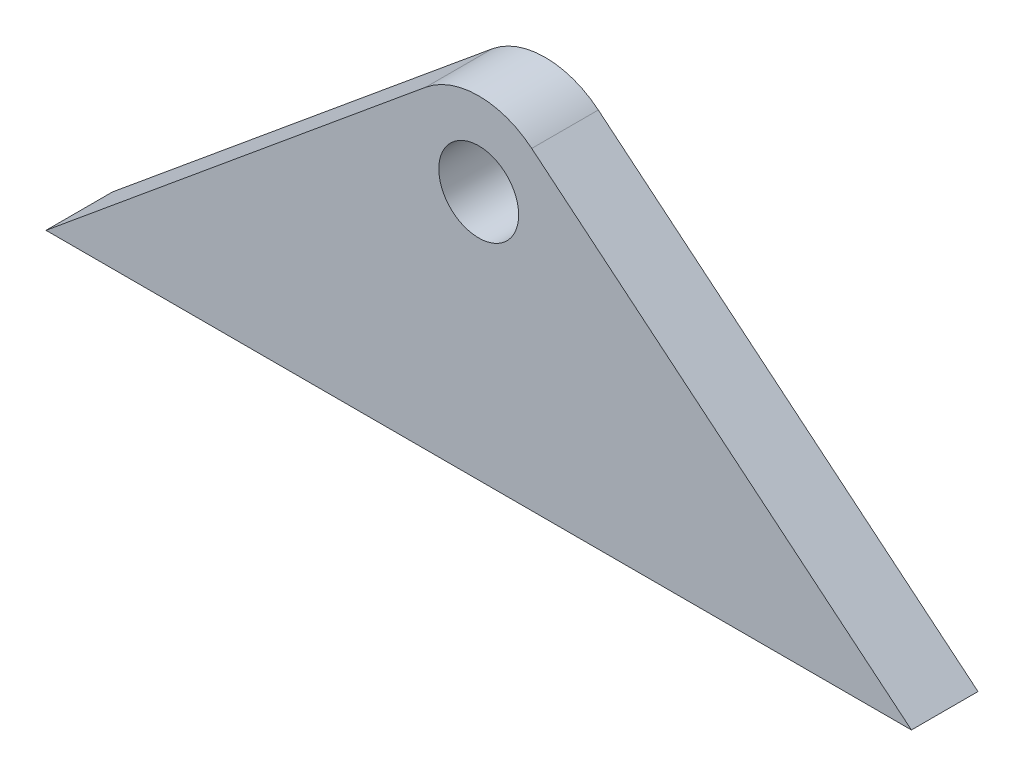
SolidWorks part; units mm, degrees
ref_plane "Front Plane" through (0, 0, 0) normal (0, 0, 1) x (1, 0, 0)
ref_plane "Top Plane" through (0, 0, 0) normal (0, 1, 0) x (1, 0, 0)
ref_plane "Right Plane" through (0, 0, 0) normal (1, 0, 0) x (0, 0, -1)
sketch "Sketch1" plane through (0, 0, 0) normal (0, 0, 1) x (1, 0, 0)
  line L0 (0, 0) -> (0, 75) construction
  line L1 (130, 0) -> (-130, 0)
  line L2 (-130, 0) -> (-15.9256, 94.2711)
  line L3 (130, 0) -> (15.9256, 94.2711)
  arc A0 (15.9256, 94.2711) -> (-15.9256, 94.2711) centre (0, 75) ccw
  circle A1 centre (0, 75) radius 12
  dimension "D3" = 25
  dimension "D4" = 24
  dimension "D1" = 260
  dimension "D2" = 75
extrude "Boss-Extrude1" add sketch "Sketch1" along normal mid plane 20
